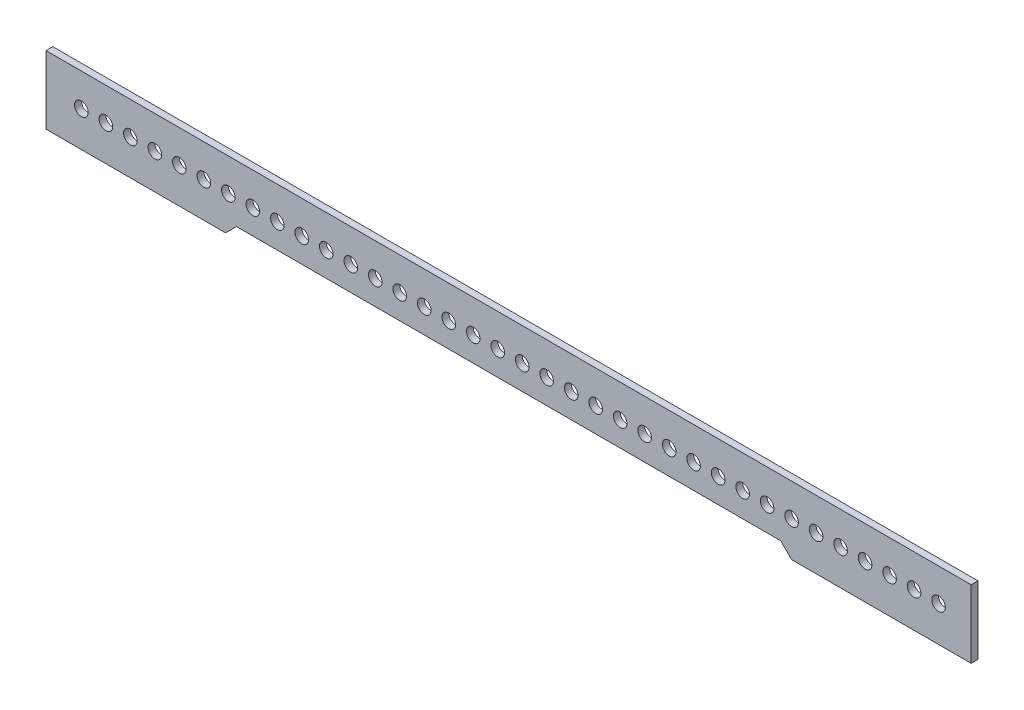
SolidWorks part; units mm, degrees
ref_plane "Front Plane" through (0, 0, 0) normal (0, 0, 1) x (1, 0, 0)
ref_plane "Top Plane" through (0, 0, 0) normal (0, 1, 0) x (1, 0, 0)
ref_plane "Right Plane" through (0, 0, 0) normal (1, 0, 0) x (0, 0, -1)
sketch "Sketch1" plane through (0, 0, 0) normal (0, 0, 1) x (1, 0, 0)
  line L0 (-215.9, 0) -> (215.9, 0)
  line L2 (215.9, -31.75) -> (132.08, -31.75)
  line L3 (132.08, -31.75) -> (127, -26.67)
  line L4 (127, -26.67) -> (-127, -26.67)
  line L5 (-127, -26.67) -> (-132.08, -31.75)
  line L6 (-132.08, -31.75) -> (-215.9, -31.75)
  line L8 (-215.9, -31.75) -> (-215.9, 0)
  line L9 (215.9, 0) -> (215.9, -31.75)
  dimension "D1" = 431.8
  dimension "D2" = 31.75
  dimension "D3" = 254
  dimension "D4" = 5.08
extrude "Boss-Extrude1" add sketch "Sketch1" along normal blind 3.175
sketch "Sketch3" plane through (0, 0, 3.175) normal (0, 0, 1) x (1, 0, 0)
  line L0 (215.9, 0) -> (-215.9, 0) construction
  line L2 (-199.39, -15.24) -> (-187.96, -15.24) construction
  line L3 (-215.9, 0) -> (-215.9, -31.75) construction
  circle A0 centre (-199.39, -15.24) radius 3.175
  circle A1 centre (-187.96, -15.24) radius 3.175
  circle A2 centre (-176.53, -15.24) radius 3.175
  circle A3 centre (-165.1, -15.24) radius 3.175
  circle A4 centre (-153.67, -15.24) radius 3.175
  circle A5 centre (-142.24, -15.24) radius 3.175
  circle A6 centre (-130.81, -15.24) radius 3.175
  circle A7 centre (-119.38, -15.24) radius 3.175
  circle A8 centre (-107.95, -15.24) radius 3.175
  circle A9 centre (-96.52, -15.24) radius 3.175
  circle A10 centre (-85.09, -15.24) radius 3.175
  circle A11 centre (-73.66, -15.24) radius 3.175
  circle A12 centre (-62.23, -15.24) radius 3.175
  circle A13 centre (-50.8, -15.24) radius 3.175
  circle A14 centre (-39.37, -15.24) radius 3.175
  circle A15 centre (-27.94, -15.24) radius 3.175
  circle A16 centre (-16.51, -15.24) radius 3.175
  circle A17 centre (-5.08, -15.24) radius 3.175
  circle A18 centre (6.35, -15.24) radius 3.175
  circle A19 centre (17.78, -15.24) radius 3.175
  circle A20 centre (29.21, -15.24) radius 3.175
  circle A21 centre (40.64, -15.24) radius 3.175
  circle A22 centre (52.07, -15.24) radius 3.175
  circle A23 centre (63.5, -15.24) radius 3.175
  circle A24 centre (74.93, -15.24) radius 3.175
  circle A25 centre (86.36, -15.24) radius 3.175
  circle A26 centre (97.79, -15.24) radius 3.175
  circle A27 centre (109.22, -15.24) radius 3.175
  circle A28 centre (120.65, -15.24) radius 3.175
  circle A29 centre (132.08, -15.24) radius 3.175
  circle A30 centre (143.51, -15.24) radius 3.175
  circle A31 centre (154.94, -15.24) radius 3.175
  circle A32 centre (166.37, -15.24) radius 3.175
  circle A33 centre (177.8, -15.24) radius 3.175
  circle A34 centre (189.23, -15.24) radius 3.175
  circle A35 centre (200.66, -15.24) radius 3.175
  dimension "D1" = 6.35
  dimension "D3" = 16.51
  dimension "D2" = 15.24
  dimension "D5" = 11.43
  dimension "D4" = 36
extrude "Cut-Extrude2" cut sketch "Sketch3" against normal through all
